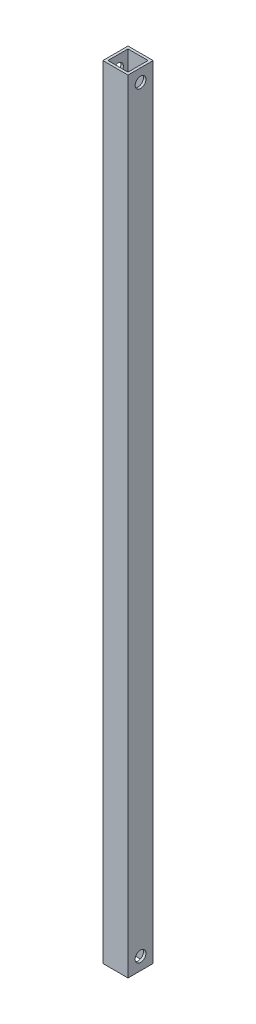
SolidWorks part; units mm, degrees
material "5052-H34"
ref_plane "正面" through (0, 0, 0) normal (0, 0, 1) x (1, 0, 0)
ref_plane "平面" through (0, 0, 0) normal (0, 1, 0) x (1, 0, 0)
ref_plane "右側面" through (0, 0, 0) normal (1, 0, 0) x (0, 0, -1)
sketch "ｽｹｯﾁ1" plane through (0, 0, 0) normal (0, 1, 0) x (1, 0, 0)
  line L1 (-5, 5) -> (5, 5)
  line L2 (-5, 5) -> (-5, -5)
  line L3 (-5, -5) -> (5, -5)
  line L4 (5, 5) -> (5, -5)
  line L5 (-5, 5) -> (5, -5) construction
  line L6 (-5, -5) -> (5, 5) construction
  point P0 (0, 0)
  dimension "D1" = 10
  dimension "D2" = 10
extrude "押し出し-薄板1" add sketch "ｽｹｯﾁ1" along normal blind 311.0187 thin
sketch "ｽｹｯﾁ2" plane through (5, 0, 0) normal (1, 0, 0) x (0, 0, -1)
  line L0 (-5, 155.5093) -> (5, 155.5093) construction
  line L1 (-5, 311.0187) -> (-5, 0) construction
  line L2 (5, 311.0187) -> (5, 0) construction
  line L3 (0, 0) -> (0, 5) construction
  circle A0 centre (0, 5) radius 2.15
  circle A1 centre (0, 306.0187) radius 2.15
  dimension "D2" = 4.3
  dimension "D1" = 5
extrude "ｶｯﾄ - 押し出し1" cut sketch "ｽｹｯﾁ2" against normal through all
equation "\"D1@押し出し-薄板1\"=10+sqr(130^2+271.5^2)"
